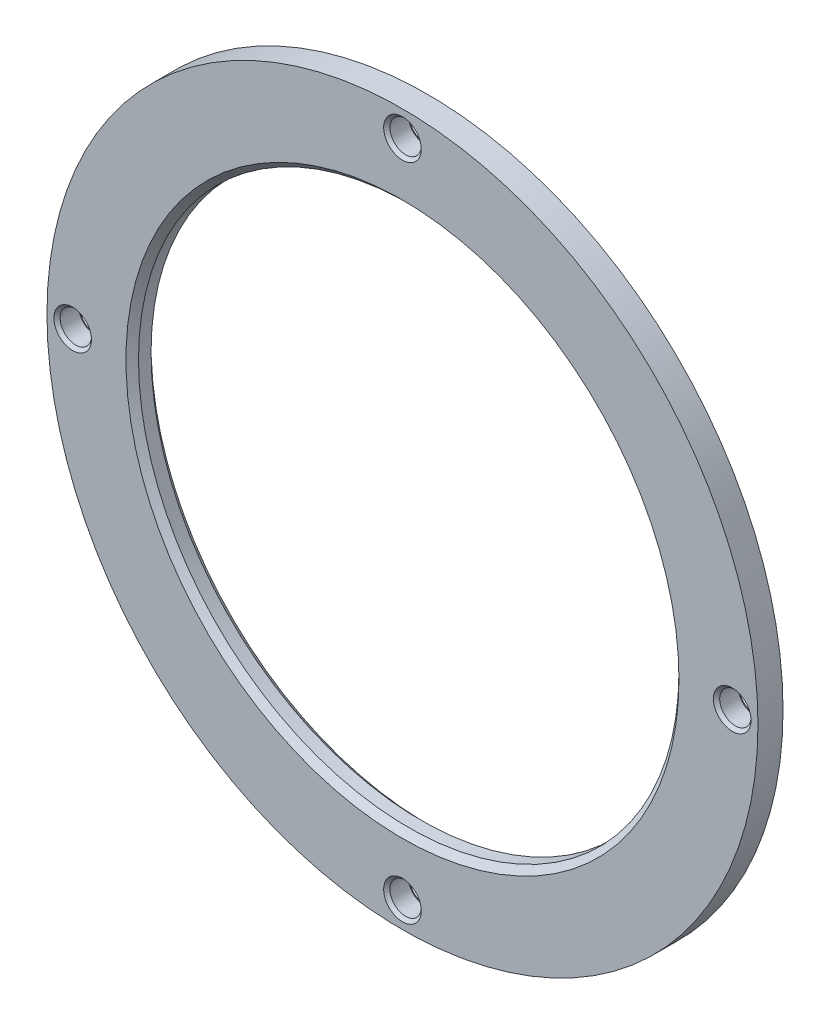
SolidWorks part; units mm, degrees
material "ABS"
ref_plane "Front Plane" through (0, 0, 0) normal (1, 0, 0) x (0, 1, 0)
ref_plane "Top Plane" through (0, 0, 0) normal (0, 0, 1) x (0, 1, 0)
ref_plane "Right Plane" through (0, 0, 0) normal (0, 1, 0) x (-1, 0, 0)
sketch "Sketch1" plane through (0, 0, 0) normal (0, 0, 1) x (0, 1, 0)
  circle A0 centre (0, 0) radius 28.35
  dimension "D1" = 56.7
extrude "Extrude-Thin1" add sketch "Sketch1" along normal blind 2 thin thin type one direction reverse wall 6.8
chamfer "Chamfer1" distance 0.5 angle 45 2 edges at (0, 21.55, 2) (0, 21.55, 0)
sketch "Sketch2" plane through (0, 0, 0) normal (0, 0, 1) x (0, 1, 0)
  circle A0 centre (0, 26.3) radius 1.25
  circle A2 centre (0, 0) radius 22.05 construction
  dimension "D1" = 26.3
  dimension "D2" = 2.5
extrude "Cut-Extrude1" cut sketch "Sketch2" along normal through all
pattern_circular "CirPattern1" count 4 over 360 about axis through (0, 0, 0) along (0, 0, 1) of "Cut-Extrude1"
chamfer "Chamfer2" distance 0.25 angle 45 8 edges at (-25.05, 0, 0) (0, 25.05, 0) (25.05, 0, 0) (0, -25.05, 0) (0, -25.05, 2) (25.05, 0, 2) (0, 25.05, 2) (-25.05, 0, 2)
